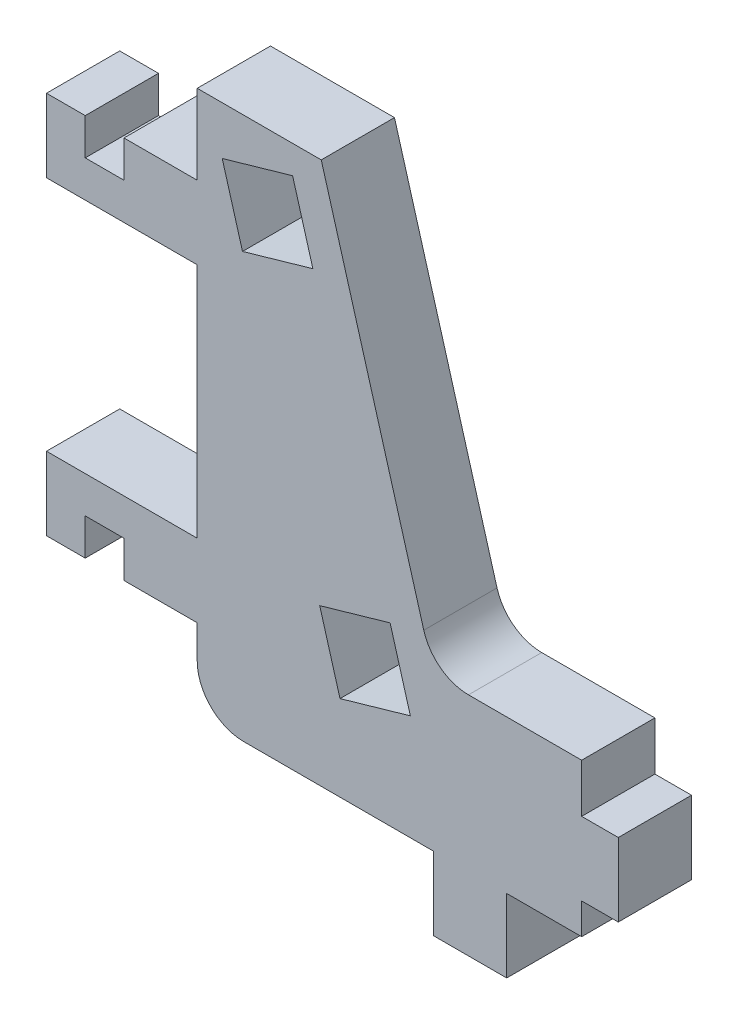
SolidWorks part; units mm, degrees
ref_plane "Front Plane" through (0, 0, 0) normal (0, 0, 1) x (1, 0, 0)
ref_plane "Top Plane" through (0, 0, 0) normal (0, 1, 0) x (1, 0, 0)
ref_plane "Right Plane" through (0, 0, 0) normal (1, 0, 0) x (0, 0, -1)
sketch "Sketch1" plane through (0, 0, 0) normal (0, 0, 1) x (1, 0, 0)
  line L0 (0, 0) -> (0, 44.45)
  line L1 (0, 22.225) -> (-18.5141, 22.225) construction
  line L2 (0, 6.525) -> (-6, 6.525)
  line L3 (-6, 6.525) -> (-6, 9.525)
  line L4 (-6, 9.525) -> (-9.175, 9.525)
  line L5 (-9.175, 9.525) -> (-9.175, 6.525)
  line L6 (-9.175, 6.525) -> (-12.35, 6.525)
  line L7 (-12.35, 6.525) -> (-12.35, 12.525)
  line L8 (-12.35, 12.525) -> (0, 12.525)
  line L9 (0, 37.925) -> (-6, 37.925)
  line L10 (-6, 37.925) -> (-6, 34.925)
  line L11 (-6, 34.925) -> (-9.175, 34.925)
  line L12 (-9.175, 34.925) -> (-9.175, 37.925)
  line L13 (-9.175, 37.925) -> (-12.35, 37.925)
  line L14 (-12.35, 37.925) -> (-12.35, 31.925)
  line L15 (-12.35, 31.925) -> (0, 31.925)
  line L16 (0, 0) -> (19.3548, 0)
  line L17 (19.3548, 0) -> (19.3548, -6)
  line L18 (19.3548, -6) -> (25.3548, -6)
  line L19 (25.3548, -6) -> (25.3548, 0)
  line L20 (25.3548, 0) -> (31.496, 0)
  line L21 (31.496, 0) -> (31.496, 2.54)
  line L22 (31.496, 2.54) -> (34.496, 2.54)
  line L23 (34.496, 2.54) -> (34.496, 8.54)
  line L24 (34.496, 8.54) -> (31.496, 8.54)
  line L25 (31.496, 8.54) -> (31.496, 12.525)
  line L26 (0, 44.45) -> (10.16, 44.45)
  line L27 (10.16, 44.45) -> (19.3548, 12.525)
  line L28 (19.3548, 12.525) -> (31.496, 12.525)
  point P13 (-12.35, 9.525)
  point P31 (32.996, 2.54)
  dimension "D1" = 44.45
  dimension "D2" = 6
  dimension "D3" = 6
  dimension "D4" = 3.175
  dimension "D5" = 3.175
  dimension "D6" = 3
  dimension "D7" = 12.7
  dimension "D8" = 19.3548
  dimension "D9" = 6
  dimension "D10" = 6
  dimension "D11" = 31.496
  dimension "D12" = 3
  dimension "D13" = 6
  dimension "D14" = 2.54
  dimension "D15" = 10.16
extrude "Boss-Extrude1" add sketch "Sketch1" along normal blind 6 contours L14 L15 L0 L9 L10 L11 L12 L13 | L28 L27 L26 L0 L16 L17 L18 L19 L20 L21 L22 L23 L24 L25 | L8 L7 L6 L5 L4 L3 L2 L0
fillet "Fillet1" radius 3.81 2 edges at (0, 0, 3) (19.3548, 12.525, 3)
sketch "Sketch3" plane through (0, 0, 6) normal (0, 0, 1) x (1, 0, 0)
  line L0 (3.7089, 34.7272) -> (10.0357, 12.7601) construction
  line L1 (10.16, 44.45) -> (18.5612, 15.2805) construction
  line L2 (3.7089, 34.7272) -> (9.4745, 36.3878)
  line L3 (3.7089, 34.7272) -> (2.0483, 40.4928)
  line L4 (9.4745, 36.3878) -> (7.814, 42.1534)
  line L5 (2.0483, 40.4928) -> (7.814, 42.1534)
  line L6 (6.8723, 23.7437) -> (15.415, 26.2041) construction
  line L7 (15.8013, 14.4207) -> (17.4619, 8.6551)
  line L8 (11.6963, 6.9945) -> (17.4619, 8.6551)
  line L9 (10.0357, 12.7601) -> (11.6963, 6.9945)
  line L10 (10.0357, 12.7601) -> (15.8013, 14.4207)
  line L11 (14.3606, 29.8653) -> (5.8178, 27.4049) construction
  dimension "D1" = 6
  dimension "D2" = 6
  dimension "D3" = 8.89
  dimension "D4" = 11.43
  dimension "D5" = 3.81
extrude "Cut-Extrude1" cut sketch "Sketch3" against normal through all
